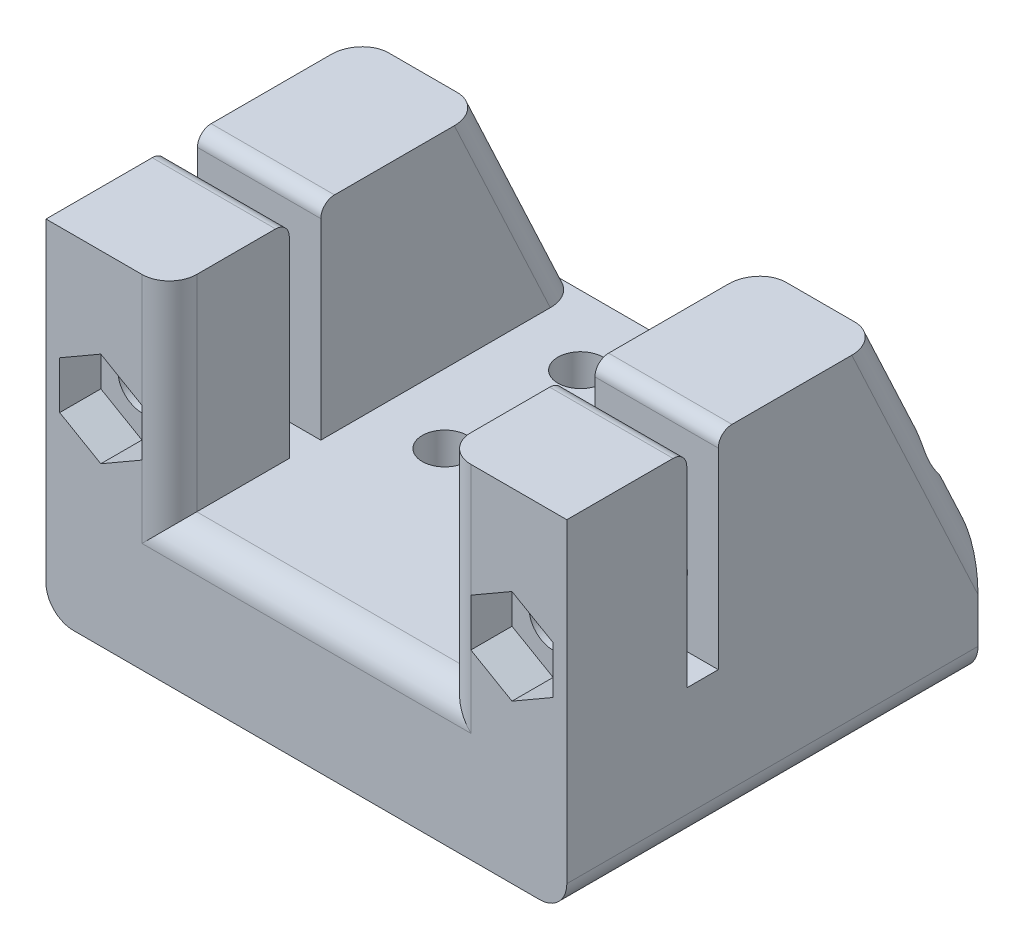
SolidWorks part; units mm, degrees
ref_plane "Спереди" through (0, 0, 0) normal (0, 0, 1) x (1, 0, 0)
ref_plane "Сверху" through (0, 0, 0) normal (0, 1, 0) x (1, 0, 0)
ref_plane "Справа" through (0, 0, 0) normal (1, 0, 0) x (0, 0, -1)
sketch "Эскиз1" plane through (0, 0, 0) normal (0, 1, 0) x (1, 0, 0)
  line L0 (12, 20) -> (19, 27) construction
  line L1 (0, 0) -> (38, 0)
  line L2 (0, 0) -> (0, 30)
  line L3 (0, 30) -> (38, 30)
  line L4 (38, 0) -> (38, 30)
  line L5 (23.9497, 15.0503) -> (14.0503, 24.9497) construction
  line L6 (14.0503, 15.0503) -> (23.9497, 24.9497) construction
  circle A0 centre (19, 20) radius 7 construction
  circle A1 centre (14.0503, 24.9497) radius 1.65
  circle A2 centre (23.9497, 24.9497) radius 1.65
  circle A3 centre (23.9497, 15.0503) radius 1.65
  circle A4 centre (14.0503, 15.0503) radius 1.65
  point P7 (0, 0)
  point P19 (19, 0)
  point P20 (0, 0)
  point P21 (14.2748, 20.9724)
  point P22 (0, 0)
  point P23 (14.28, 20.965)
  dimension "D1" = 38
  dimension "D3" = 14
  dimension "D5" = 3.3
  dimension "D2" = 30
  dimension "D4" = 20
extrude "Основа" add sketch "Эскиз1" along normal blind 25
sketch "Эскиз3" plane through (0, 25, 0) normal (0, 1, 0) x (1, 0, 0)
  line L0 (38, 30) -> (0, 30) construction
  line L1 (9, 30) -> (29, 30)
  line L2 (9, 30) -> (9, 0)
  line L3 (9, 0) -> (29, 0)
  line L4 (29, 30) -> (29, 0)
  line L5 (0, 0) -> (38, 0) construction
  point P8 (-27.2493, 30)
  point P9 (19, 30)
  point P10 (19, 30)
  dimension "D1" = 20
extrude "Центральный вырез" cut sketch "Эскиз3" against normal blind 15
sketch "Эскиз4" plane through (0, 0, 0) normal (-1, 0, 0) x (0, 0, 1)
  line L0 (-30, 10) -> (-23, 25)
  line L1 (-30, 25) -> (0, 25) construction
  line L3 (-30, 10) -> (-30, 25)
  line L6 (-30, 25) -> (-23, 25)
  line L9 (-11.0503, 25) -> (-11.0503, 10)
  line L10 (-11.0503, 10) -> (-8.7503, 10)
  line L11 (-8.7503, 10) -> (-8.7503, 25)
  line L12 (-8.7503, 25) -> (-11.0503, 25)
  line L14 (-15.0503, 10) -> (-15.0503, 0) construction
  point P0 (-24.121, 25)
  dimension "D1" = 7
  dimension "D3" = 2.3
  dimension "D4" = 4
  dimension "D5" = 15
extrude "вырез под пластину" cut sketch "Эскиз4" against normal through all
fillet "Скругление3" radius 1 4 edges at (4.5, 25, -8.7503) (33.5, 25, -8.7503) (33.5, 25, -11.0503) (4.5, 25, -11.0503)
fillet "Скругление4" radius 2 9 edges at (0, 0, -15) (38, 0, -15) (19, 10, 0) (9, 17.5, 0) (29, 17.5, 0) (29, 17.5, -26.5) (38, 17.5, -26.5) (0, 17.5, -26.5) (9, 17.5, -26.5)
sketch "Эскиз6" plane through (0, 0, -30) normal (0, 0, -1) x (-1, 0, 0)
  line L1 (-34, 15) -> (-4, 15) construction
  line L2 (-31, 10) -> (-7, 10) construction
  line L3 (-36, 0) -> (-2, 0) construction
  circle A0 centre (-34, 15) radius 1.75
  circle A1 centre (-4, 15) radius 1.75
  point P6 (-19, 15)
  point P9 (-19, 0)
  dimension "D1" = 3.5
  dimension "D2" = 5
  dimension "D3" = 30
extrude "Отверстия под болты" cut sketch "Эскиз6" against normal through all
sketch "Эскиз7" plane through (0, 0, -30) normal (0, 0, -1) x (-1, 0, 0)
  circle A0 centre (-34, 15) radius 3.5
  circle A1 centre (-4, 15) radius 3.5
  dimension "D1" = 7
extrude "Углубления под шляпки" cut sketch "Эскиз7" against normal blind 10
sketch "Эскиз8" plane through (0, 0, 0) normal (0, 0, 1) x (1, 0, 0)
  line L1 (7, 13.2679) -> (7, 16.7321)
  line L2 (7, 16.7321) -> (4, 18.4641)
  line L3 (4, 18.4641) -> (1, 16.7321)
  line L4 (1, 16.7321) -> (1, 13.2679)
  line L5 (1, 13.2679) -> (4, 11.5359)
  line L6 (4, 11.5359) -> (7, 13.2679)
  line L13 (34, 18.4641) -> (31, 16.7321)
  line L14 (31, 16.7321) -> (31, 13.2679)
  line L15 (31, 13.2679) -> (34, 11.5359)
  line L16 (34, 11.5359) -> (37, 13.2679)
  line L17 (37, 13.2679) -> (37, 16.7321)
  line L18 (37, 16.7321) -> (34, 18.4641)
  circle A0 centre (4, 15) radius 3 construction
  circle A1 centre (34, 15) radius 3 construction
  point P1 (0, 0)
  dimension "D1" = 6
extrude "Углубления под гайки" cut sketch "Эскиз8" against normal blind 3
